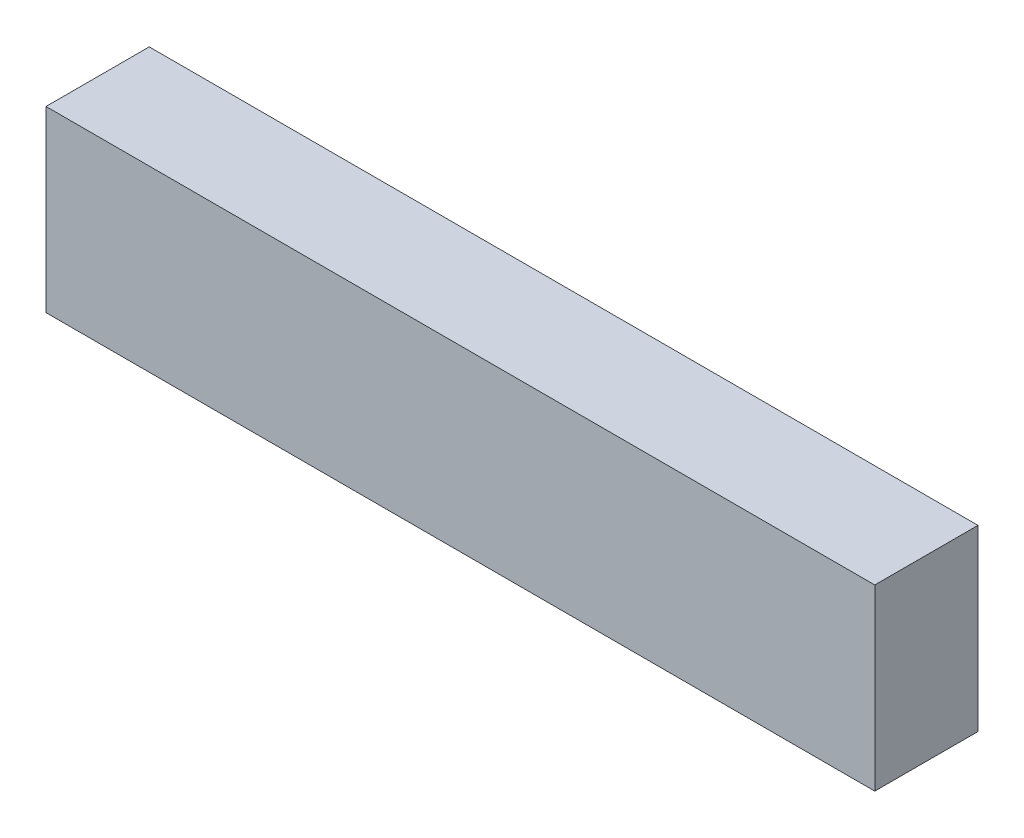
SolidWorks part; units mm, degrees
ref_plane "Front Plane" through (0, 0, 0) normal (0, 0, 1) x (1, 0, 0)
ref_plane "Top Plane" through (0, 0, 0) normal (0, 1, 0) x (1, 0, 0)
ref_plane "Right Plane" through (0, 0, 0) normal (1, 0, 0) x (0, 0, -1)
sketch "Sketch1" plane through (0, 0, 0) normal (0, 0, 1) x (1, 0, 0)
  line L0 (7.6645, -17.43) -> (66.2645, -17.43) construction
  line L1 (7.8645, -17.63) -> (66.0645, -17.63)
  line L2 (7.8645, -17.63) -> (7.8645, -30.17)
  line L3 (7.8645, -30.17) -> (66.0645, -30.17)
  line L4 (66.0645, -17.63) -> (66.0645, -30.17)
  line L5 (66.2645, -17.43) -> (66.2645, -30.37) construction
  line L6 (66.2645, -30.37) -> (7.6645, -30.37) construction
  line L7 (7.6645, -30.37) -> (7.6645, -17.43) construction
  dimension "D1" = 0.2
  dimension "D2" = 0.2
  dimension "D3" = 0.2
  dimension "D4" = 0.2
extrude "Boss-Extrude1" add sketch "Sketch1" along normal blind 7.25
shell "Shell1" thickness 0.5
equation "\"D2@Sketch1\"=\"D1@Sketch1\""
equation "\"D3@Sketch1\"=\"D1@Sketch1\""
equation "\"D4@Sketch1\"=\"D1@Sketch1\""
